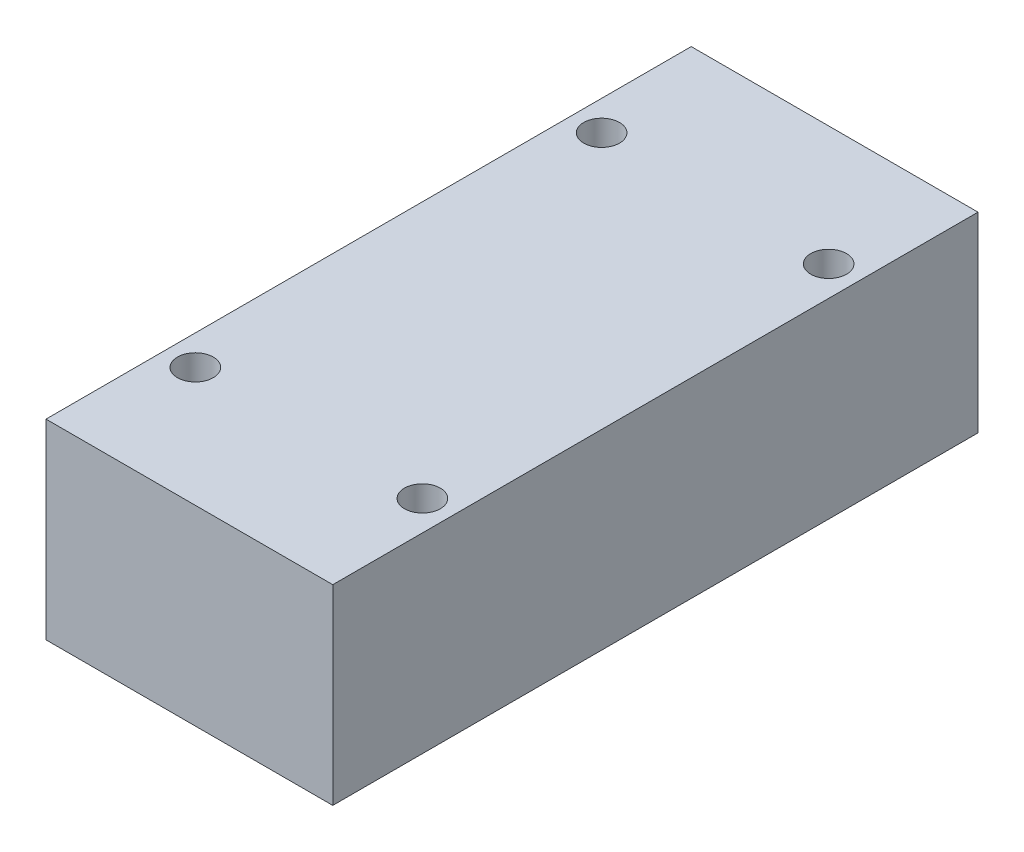
SolidWorks part; units mm, degrees
ref_plane "前视基准面" through (0, 0, 0) normal (0, 0, 1) x (1, 0, 0)
ref_plane "上视基准面" through (0, 0, 0) normal (0, 1, 0) x (1, 0, 0)
ref_plane "右视基准面" through (0, 0, 0) normal (1, 0, 0) x (0, 0, -1)
sketch "草图1" plane through (0, 0, 0) normal (0, 0, 1) x (1, 0, 0)
  line L0 (0, 30.199) -> (0, -24.5864) construction
  line L1 (-32.0838, 0) -> (36.6073, 0) construction
  line L2 (12, 8) -> (-12, 8)
  line L3 (-12, 8) -> (-12, -8)
  line L4 (12, 8) -> (12, -8)
  line L5 (12, -8) -> (-12, -8)
  point P5 (0, -8)
  point P10 (0, 8)
  point P12 (12, 0)
  point P13 (-12, 0)
  dimension "D1" = 16
  dimension "D2" = 24
extrude "凸台-拉伸1" add sketch "草图1" along normal mid plane 54
sketch "Sketch1" plane through (0, 8, 0) normal (0, 1, 0) x (1, 0, 0)
  line L0 (0, 43.0013) -> (0, -44.4916) construction
  line L1 (-30.3316, 0) -> (22.8625, 0) construction
  line L2 (12, 27) -> (-12, 27) construction
  line L3 (12, -27) -> (12, 27) construction
  circle A0 centre (-9.5, 17) radius 1.5
  circle A1 centre (9.5, 17) radius 1.5
  circle A2 centre (9.5, -17) radius 1.5
  circle A3 centre (-9.5, -17) radius 1.5
  dimension "D1" = 3
  dimension "D2" = 10
  dimension "D3" = 2.5
extrude "Cut-Extrude1" cut sketch "Sketch1" against normal through all
